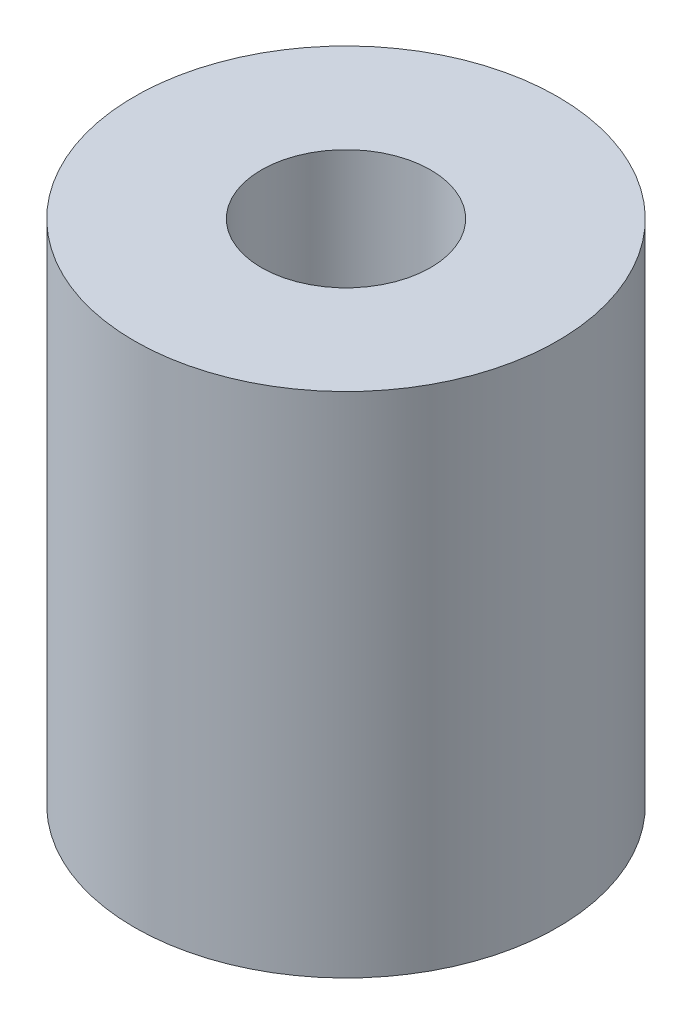
SolidWorks part; units mm, degrees
material "PETG"
ref_plane "Front Plane" through (0, 0, 0) normal (0, 0, 1) x (1, 0, 0)
ref_plane "Top Plane" through (0, 0, 0) normal (0, 1, 0) x (1, 0, 0)
ref_plane "Right Plane" through (0, 0, 0) normal (1, 0, 0) x (0, 0, -1)
sketch "Sketch1" plane through (0, 0, 0) normal (0, 1, 0) x (1, 0, 0)
  circle A0 centre (0, 0) radius 2
  circle A1 centre (0, 0) radius 5
  dimension "D1" = 4
  dimension "D2" = 10
extrude "Boss-Extrude1" add sketch "Sketch1" along normal blind 12
